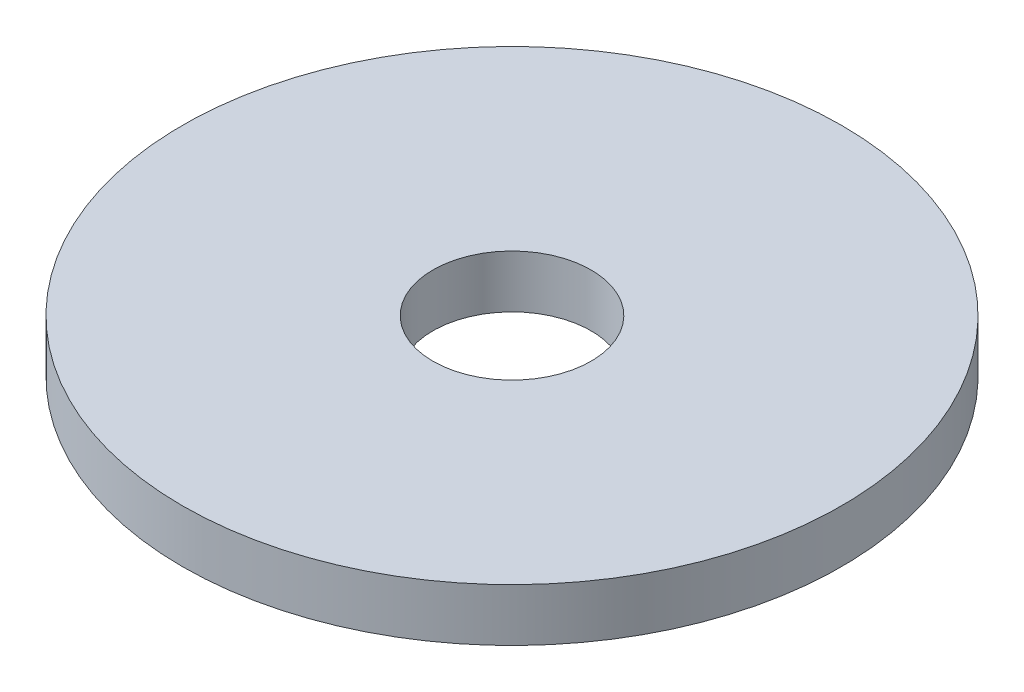
SolidWorks part; units mm, degrees
ref_plane "Front Plane" through (0, 0, 0) normal (0, 0, 1) x (1, 0, 0)
ref_plane "Top Plane" through (0, 0, 0) normal (0, 1, 0) x (1, 0, 0)
ref_plane "Right Plane" through (0, 0, 0) normal (1, 0, 0) x (0, 0, -1)
sketch "Sketch1" plane through (0, 0, 0) normal (0, 1, 0) x (1, 0, 0)
  circle A0 centre (0, 0) radius 6.25
  circle A1 centre (0, 0) radius 1.5
  dimension "D1" = 12.5
  dimension "D2" = 3
extrude "Boss-Extrude1" add sketch "Sketch1" along normal blind 1
